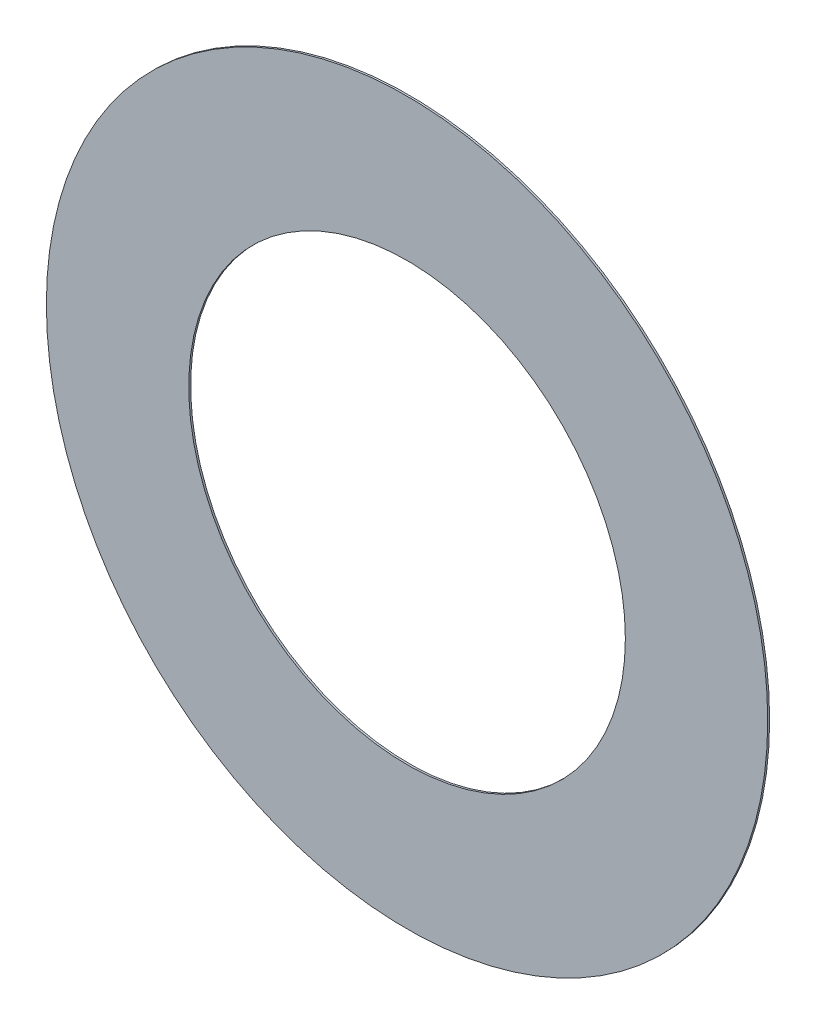
SolidWorks part; units mm, degrees
ref_plane "Front Plane" through (0, 0, 0) normal (0, 0, 1) x (1, 0, 0)
ref_plane "Top Plane" through (0, 0, 0) normal (0, 1, 0) x (1, 0, 0)
ref_plane "Right Plane" through (0, 0, 0) normal (1, 0, 0) x (0, 0, -1)
sketch "Sketch1" plane through (0, 0, 0) normal (0, 0, 1) x (1, 0, 0)
  circle A0 centre (-57.16, 27) radius 19
  circle A2 centre (-57.16, 27) radius 19 construction
  circle A3 centre (-57.16, 27) radius 11.5
  circle A4 centre (-57.16, 27) radius 11.5 construction
extrude "Extrude1" add sketch "Sketch1" along normal blind 0.1
